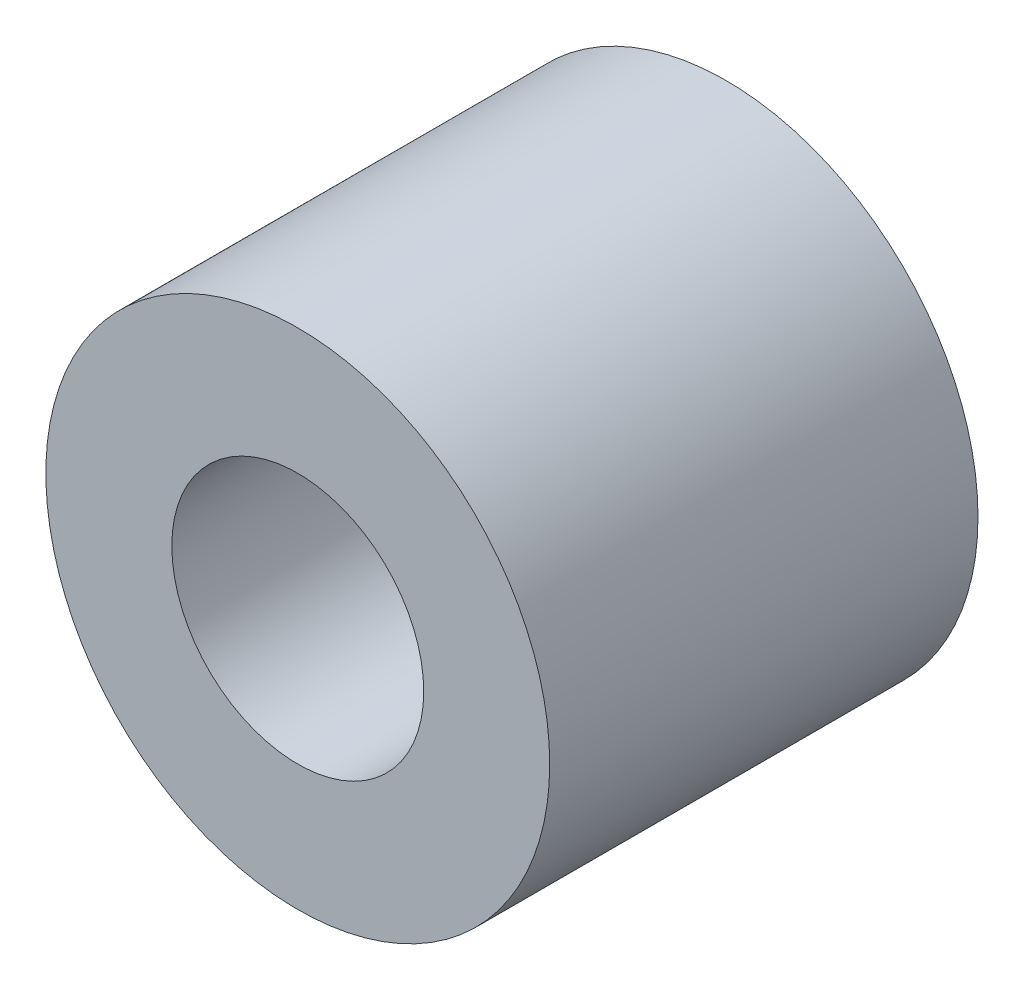
SolidWorks part; units mm, degrees
material "可鍛不銹鋼"
ref_plane "前基準面" through (0, 0, 0) normal (0, 0, 1) x (1, 0, 0)
ref_plane "上基準面" through (0, 0, 0) normal (0, 1, 0) x (1, 0, 0)
ref_plane "右基準面" through (0, 0, 0) normal (1, 0, 0) x (0, 0, -1)
sketch "草圖1" plane through (0, 0, 0) normal (0, 0, 1) x (1, 0, 0)
  circle A0 centre (0, 0) radius 5
  circle A1 centre (0, 0) radius 2.5
  dimension "D1" = 5
  dimension "D2" = 10
extrude "伸長1" add sketch "草圖1" along normal blind 8.5
